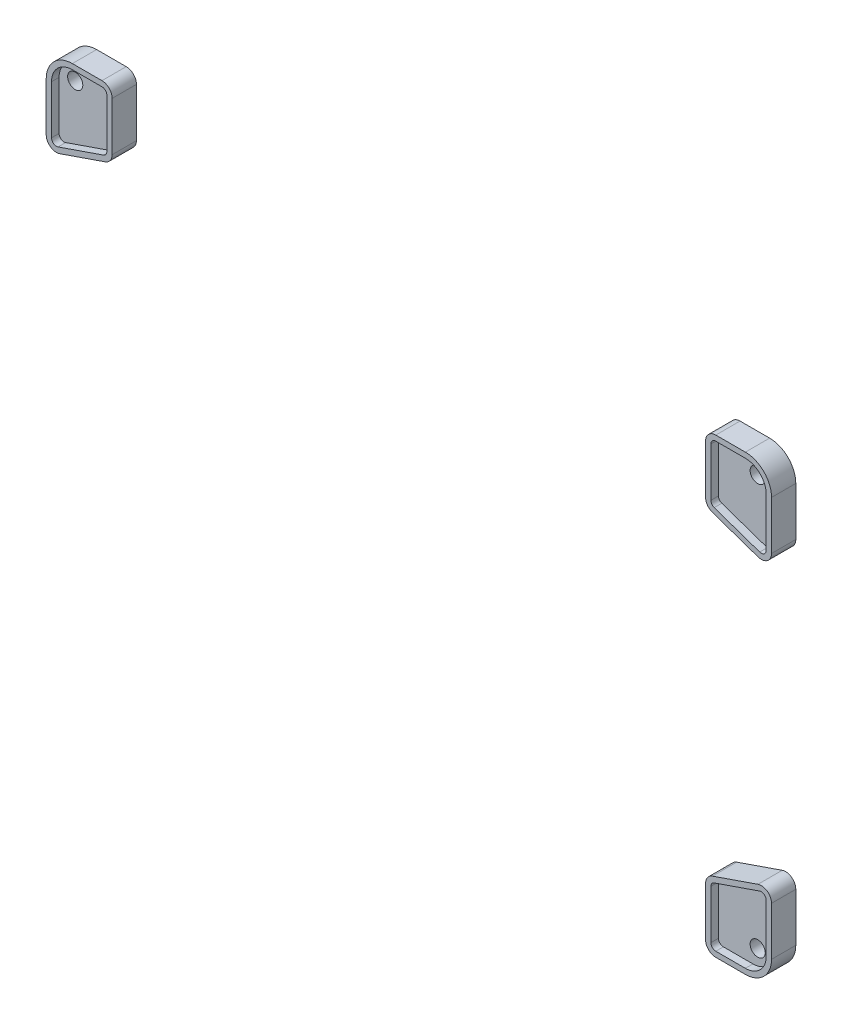
SolidWorks part; units mm, degrees
ref_plane "Front Plane" through (0, 0, 0) normal (0, 0, 1) x (1, 0, 0)
ref_plane "Top Plane" through (0, 0, 0) normal (0, 1, 0) x (1, 0, 0)
ref_plane "Right Plane" through (0, 0, 0) normal (1, 0, 0) x (0, 0, -1)
sketch "Sketch1" plane through (0, 0, 0) normal (0, 0, 1) x (1, 0, 0)
  line L0 (47.825, 19.975) -> (47.825, 26.375)
  line L1 (44.375, 29.825) -> (40.475, 29.825)
  line L2 (39.125, 28.475) -> (39.125, 22.0444)
  line L3 (40.0348, 20.7681) -> (46.0348, 18.6988)
  line L4 (47.975, 19.975) -> (47.975, 26.375)
  line L5 (44.375, 29.975) -> (40.475, 29.975)
  line L6 (38.975, 28.475) -> (38.975, 22.0444)
  line L7 (39.9859, 20.6263) -> (45.9859, 18.557)
  line L8 (47.975, 19.975) -> (47.975, 26.375) construction
  line L9 (44.375, 29.975) -> (40.475, 29.975) construction
  line L10 (38.975, 28.475) -> (38.975, 22.0444) construction
  line L11 (39.9859, 20.6263) -> (45.9859, 18.557) construction
  arc A0 (47.825, 26.375) -> (44.375, 29.825) centre (44.375, 26.375) ccw
  arc A1 (40.475, 29.825) -> (39.125, 28.475) centre (40.475, 28.475) ccw
  arc A2 (39.125, 22.0444) -> (40.0348, 20.7681) centre (40.475, 22.0444) ccw
  arc A3 (46.0348, 18.6988) -> (47.825, 19.975) centre (46.475, 19.975) ccw
  arc A4 (45.9859, 18.557) -> (47.975, 19.975) centre (46.475, 19.975) ccw
  arc A5 (47.975, 26.375) -> (44.375, 29.975) centre (44.375, 26.375) ccw
  arc A6 (40.475, 29.975) -> (38.975, 28.475) centre (40.475, 28.475) ccw
  arc A7 (38.975, 22.0444) -> (39.9859, 20.6263) centre (40.475, 22.0444) ccw
  arc A8 (45.9859, 18.557) -> (47.975, 19.975) centre (46.475, 19.975) ccw construction
  arc A9 (47.975, 26.375) -> (44.375, 29.975) centre (44.375, 26.375) ccw construction
  arc A10 (40.475, 29.975) -> (38.975, 28.475) centre (40.475, 28.475) ccw construction
  arc A11 (38.975, 22.0444) -> (39.9859, 20.6263) centre (40.475, 22.0444) ccw construction
  point P24 (39.5204, 29.4296)
  point P25 (47.2587, 18.8757)
  point P26 (46.8145, 28.8145)
  point P27 (39.3757, 21.2607)
  dimension "D7" = 1.35
  dimension "D5" = 8.7
  dimension "D6" = 9.0569
  dimension "D1" = 0
  dimension "D2" = 0.15
extrude "Boss-Extrude1" add sketch "Sketch1" along normal blind 3.2
sketch "Sketch2" plane through (0, 0, 3.2) normal (0, 0, 1) x (1, 0, 0)
  line L0 (47.125, 19.975) -> (47.125, 26.375)
  line L1 (44.375, 29.125) -> (40.475, 29.125)
  line L2 (39.825, 28.475) -> (39.825, 22.0444)
  line L3 (40.2631, 21.4299) -> (46.2631, 19.3605)
  line L4 (47.825, 19.975) -> (47.825, 26.375)
  line L5 (44.375, 29.825) -> (40.475, 29.825)
  line L6 (39.125, 28.475) -> (39.125, 22.0444)
  line L7 (40.0348, 20.7681) -> (46.0348, 18.6988)
  line L8 (47.825, 19.975) -> (47.825, 26.375)
  line L9 (44.375, 29.825) -> (40.475, 29.825)
  line L10 (39.125, 28.475) -> (39.125, 22.0444)
  line L11 (40.0348, 20.7681) -> (46.0348, 18.6988)
  arc A0 (47.125, 26.375) -> (44.375, 29.125) centre (44.375, 26.375) ccw
  arc A1 (40.475, 29.125) -> (39.825, 28.475) centre (40.475, 28.475) ccw
  arc A2 (39.825, 22.0444) -> (40.2631, 21.4299) centre (40.475, 22.0444) ccw
  arc A3 (46.2631, 19.3605) -> (47.125, 19.975) centre (46.475, 19.975) ccw
  arc A4 (46.0348, 18.6988) -> (47.825, 19.975) centre (46.475, 19.975) ccw
  arc A5 (47.825, 26.375) -> (44.375, 29.825) centre (44.375, 26.375) ccw
  arc A6 (40.475, 29.825) -> (39.125, 28.475) centre (40.475, 28.475) ccw
  arc A7 (39.125, 22.0444) -> (40.0348, 20.7681) centre (40.475, 22.0444) ccw
  arc A8 (46.0348, 18.6988) -> (47.825, 19.975) centre (46.475, 19.975) ccw
  arc A9 (47.825, 26.375) -> (44.375, 29.825) centre (44.375, 26.375) ccw
  arc A10 (40.475, 29.825) -> (39.125, 28.475) centre (40.475, 28.475) ccw
  arc A11 (39.125, 22.0444) -> (40.0348, 20.7681) centre (40.475, 22.0444) ccw
  dimension "D1" = 0
  dimension "D2" = 0.7
extrude "Cut-Extrude1" cut sketch "Sketch2" against normal blind 1 contours L3 A3 L0 A0 L1 A1 L2 A2
sketch "Sketch4" plane through (0, 0, 0) normal (0, 0, -1) x (-1, 0, 0)
  line L0 (-47.825, 19.975) -> (-47.825, 26.375) construction
  line L1 (-44.375, 29.825) -> (-40.475, 29.825) construction
  circle A1 centre (-45, 27.04) radius 1
  point P1 (-45, 27.04)
  point P8 (0, 0)
  dimension "D3" = 2
  dimension "D1" = 2.825
  dimension "D2" = 2.785
extrude "Cut-Extrude2" cut sketch "Sketch4" against normal through all
mirror "Mirror2" about plane through (0, 0, 0) normal (0, 1, 0) of bodies 103
mirror "Mirror3" about plane through (0, 0, 0) normal (1, 0, 0) of bodies 103
